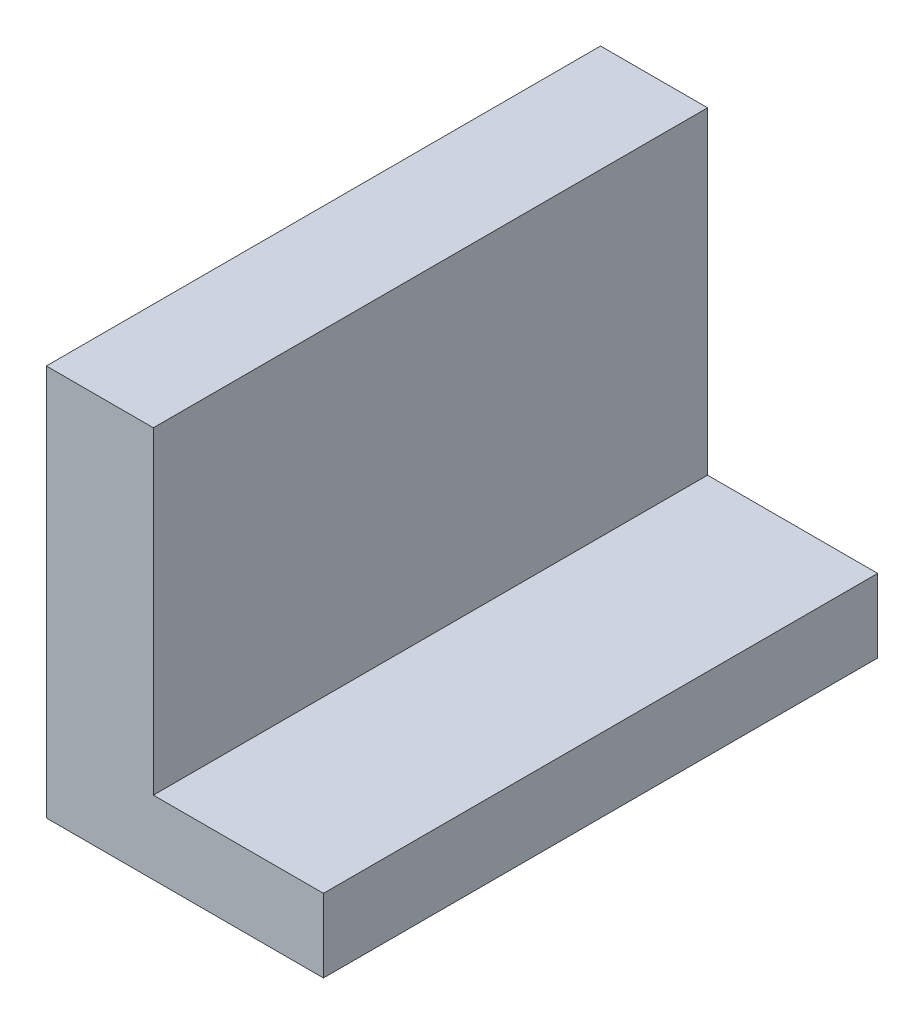
SolidWorks part; units mm, degrees
ref_plane "Front Plane" through (0, 0, 0) normal (0, 0, 1) x (1, 0, 0)
ref_plane "Top Plane" through (0, 0, 0) normal (0, 1, 0) x (1, 0, 0)
ref_plane "Right Plane" through (0, 0, 0) normal (1, 0, 0) x (0, 0, -1)
sketch "Sketch1" plane through (0, 0, 0) normal (0, 0, 1) x (1, 0, 0)
  line L0 (0, 0) -> (60, 0)
  line L1 (60, 0) -> (60, 15.873)
  line L2 (60, 15.873) -> (23.1746, 15.873)
  line L3 (23.1746, 15.873) -> (23.1746, 84.7619)
  line L4 (23.1746, 84.7619) -> (0, 84.7619)
  line L5 (0, 84.7619) -> (0, 0)
  dimension "D1" = 60
extrude "Boss-Extrude1" add sketch "Sketch1" along normal blind 120
